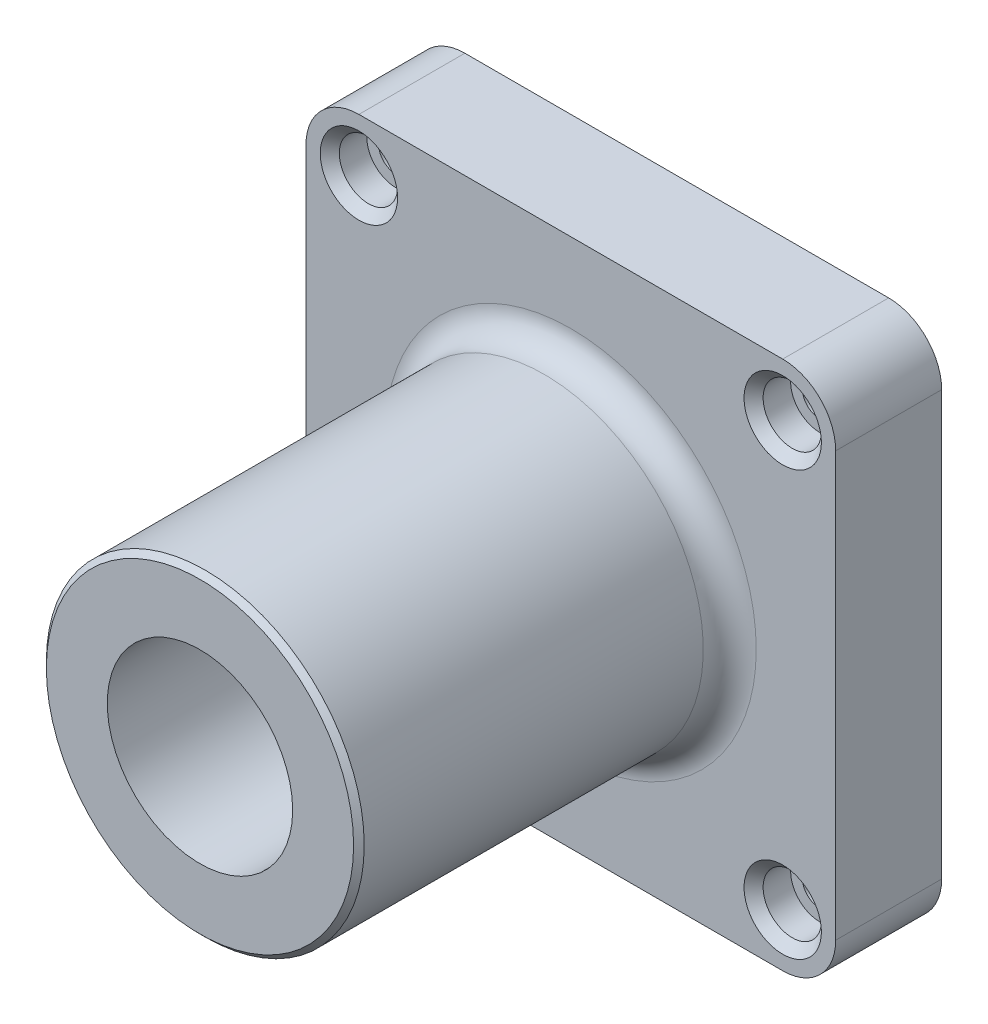
SolidWorks part; units mm, degrees
ref_plane "Front Plane" through (0, 0, 0) normal (0, 0, 1) x (1, 0, 0)
ref_plane "Top Plane" through (0, 0, 0) normal (0, 1, 0) x (1, 0, 0)
ref_plane "Right Plane" through (0, 0, 0) normal (1, 0, 0) x (0, 0, -1)
sketch "Sketch1" plane through (0, 0, 0) normal (0, 0, 1) x (1, 0, 0)
  line L1 (0, 0) -> (100, 0)
  line L2 (0, 0) -> (0, 100)
  line L3 (0, 100) -> (100, 100)
  line L4 (100, 0) -> (100, 100)
  dimension "D1" = 100
  dimension "D2" = 100
extrude "Boss-Extrude1" add sketch "Sketch1" along normal blind 20
sketch "Sketch2" plane through (0, 0, 20) normal (0, 0, 1) x (1, 0, 0)
  line L0 (50, 100) -> (50, 0) construction
  line L1 (100, 100) -> (0, 100) construction
  line L2 (0, 0) -> (100, 0) construction
  circle A0 centre (50, 50) radius 30
  dimension "D1" = 60
extrude "Boss-Extrude2" add sketch "Sketch2" along normal blind 70
fillet "Fillet1" radius 5 1 edges at (80, 50, 20)
sketch "Sketch3" plane through (0, 0, 0) normal (0, -1, 0) x (1, 0, 0)
  line L0 (80, 25) -> (80, 89)
  dimension "D1" = 64
sketch "Sketch4" plane through (0, 0, 90) normal (0, 0, 1) x (1, 0, 0)
  line L0 (20, 50) -> (80, 50) construction
  circle A0 centre (50, 50) radius 30 construction
  circle A1 centre (50, 50) radius 30 construction
  circle A2 centre (50, 50) radius 17.5
  dimension "D1" = 35
chamfer "Chamfer1" distance 1 angle 45 1 edges at (80, 50, 90)
fillet "Fillet2" radius 10 4 edges at (100, 100, 10) (100, 0, 10) (0, 0, 10) (0, 100, 10)
sketch "Sketch10" plane through (0, 0, 20) normal (0, 0, 1) x (1, 0, 0)
  line L0 (10, 90) -> (10, 10) construction
  line L1 (10, 100) -> (10, 90) construction
  line L2 (50, 100) -> (50, 0) construction
  line L3 (90, 100) -> (10, 100) construction
  line L4 (10, 0) -> (90, 0) construction
  circle A0 centre (10, 10) radius 5.5
  circle A1 centre (10, 90) radius 5.5
  arc A2 (10, 100) -> (0, 90) centre (10, 90) ccw construction
  circle A3 centre (90, 10) radius 5.5
  circle A4 centre (90, 90) radius 5.5
  dimension "D1" = 11
  dimension "D2" = 80
hole_wizard "CBORE for M6 Hex Head Bolt4" positions "3DSketch4" profile "Sketch15" counterbore size "M6" standard "ANSI Metric" end condition through all
sketch3d "3DSketch4"
  point P0 (10, 90, 20)
  point P3 (10, 10, 20)
  point P6 (90, 10, 20)
  point P9 (90, 90, 20)
sketch "Sketch15" plane through (10, 90, 20) normal (1, 0, 0) x (0, -1, 0)
  line L0 (0, 0) -> (0, 20)
  line L1 (0, 20) -> (3.3, 20)
  line L3 (3.3, 20) -> (3.3, 7)
  line L4 (5.5, 7) -> (3.3, 7)
  line L5 (5.5, 7) -> (5.5, 1.8)
  line L6 (5.5, 1.8) -> (7.3, 0)
  line L7 (7.3, 0) -> (0, 0)
  line L8 (-5.5, 1.8) -> (-7.3, 0) construction
  line L11 (0, -6.35) -> (0, 107.95) construction
  dimension "Thru Hole Dia." = 6.6
  dimension "Thru Hole Depth" = 20
  dimension "C'Bore Dia." = 11
  dimension "C'Bore Depth" = 7
  dimension "Near C'Sink Dia." = 14.6
  dimension "Near C'Sink Angle" = 90
extrude "Cut-Extrude1" cut sketch "Sketch4" against normal blind 40
sketch "Sketch16" plane through (0, 0, 50) normal (0, 0, 1) x (1, 0, 0)
  line L0 (50, 100) -> (50, 0) construction
  circle A0 centre (50, 50) radius 22.5
  dimension "D1" = 45
extrude "Cut-Extrude2" cut sketch "Sketch16" against normal blind 50
